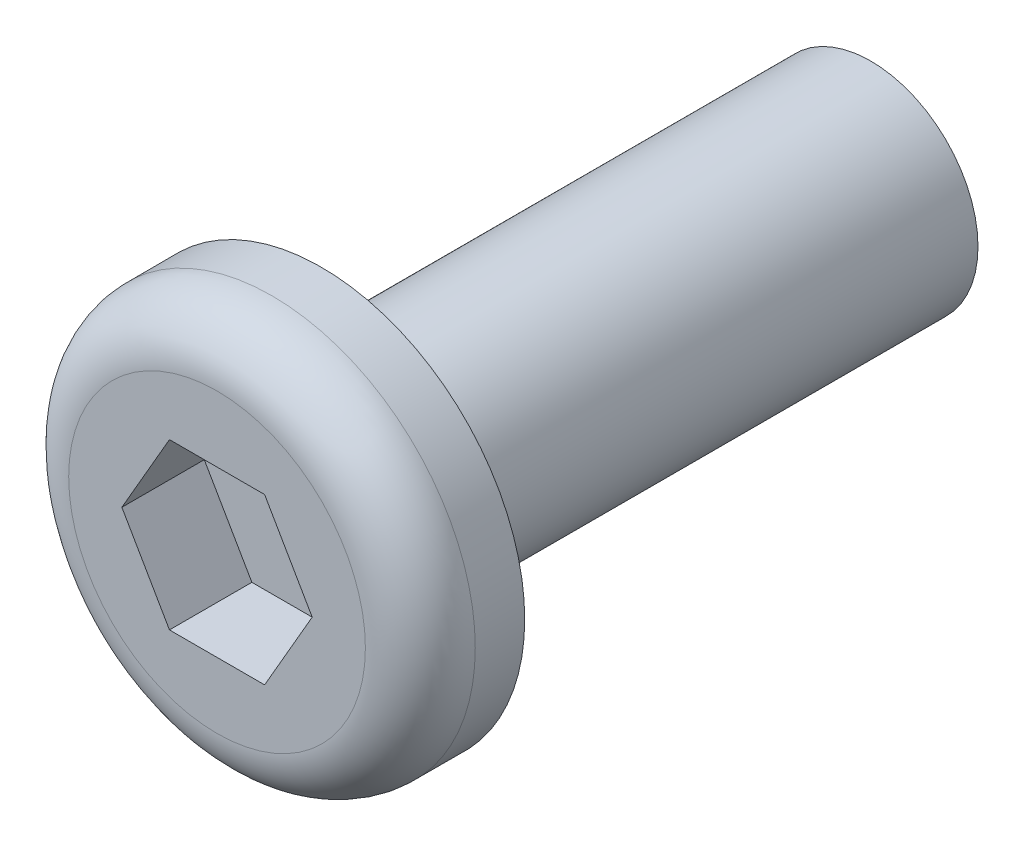
SolidWorks part; units mm, degrees
material "Chrome Stainless Steel"
ref_plane "Front Plane" through (0, 0, 0) normal (0, 0, 1) x (1, 0, 0)
ref_plane "Top Plane" through (0, 0, 0) normal (0, 1, 0) x (1, 0, 0)
ref_plane "Right Plane" through (0, 0, 0) normal (1, 0, 0) x (0, 0, -1)
sketch "Sketch1" plane through (0, 0, 0) normal (1, 0, 0) x (0, 0, -1)
  line L0 (1.9, 1.95) -> (1.9, 3.7)
  line L1 (0, 0) -> (11.9, 0)
  line L3 (1.9, 1.95) -> (11.9, 1.95)
  line L4 (11.9, 0) -> (11.9, 1.95)
  line L5 (1.9, 3.7) -> (0, 3.7)
  line L6 (0, 3.7) -> (0, 0)
  dimension "D1" = 10
  dimension "D2" = 1.95
  dimension "D3" = 3.7
  dimension "D4" = 1.9
revolve "Revolve1" add sketch "Sketch1" angle 360 about L1
fillet "Fillet1" radius 1 1 edges at (3.7, 0, 0)
sketch "Sketch2" plane through (0, 0, 0) normal (0, 0, 1) x (1, 0, 0)
  line L0 (55, 0) -> (-55, 0) construction
  line L1 (-1.7321, 0) -> (-0.866, -1.5)
  line L2 (-0.866, -1.5) -> (0.866, -1.5)
  line L3 (0.866, -1.5) -> (1.7321, 0)
  line L4 (1.7321, 0) -> (0.866, 1.5)
  line L5 (0.866, 1.5) -> (-0.866, 1.5)
  line L6 (-0.866, 1.5) -> (-1.7321, 0)
  circle A0 centre (0, 0) radius 1.5 construction
  dimension "D1" = 3
extrude "Cut-Extrude1" cut sketch "Sketch2" against normal blind 1.5
